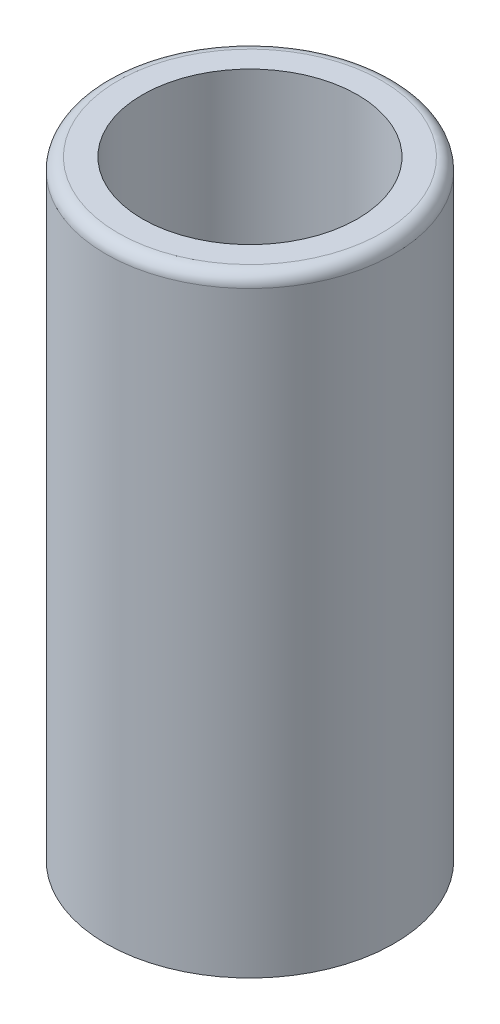
SolidWorks part; units mm, degrees
ref_plane "Front Plane" through (0, 0, 0) normal (0, 0, 1) x (1, 0, 0)
ref_plane "Top Plane" through (0, 0, 0) normal (0, 1, 0) x (1, 0, 0)
ref_plane "Right Plane" through (0, 0, 0) normal (1, 0, 0) x (0, 0, -1)
sketch "Sketch1" plane through (0, 0, 0) normal (0, 1, 0) x (1, 0, 0)
  circle A0 centre (0, 0) radius 11.825
  dimension "D1" = 23.65
extrude "Main Structure" add sketch "Sketch1" along normal blind 50
sketch "Sketch2" plane through (0, 50, 0) normal (0, 1, 0) x (1, 0, 0)
  circle A0 centre (0, 0) radius 8.825
  dimension "D1" = 17.65
extrude "Hole" cut sketch "Sketch2" against normal blind 15.5
fillet "Structure Fillet" radius 1 1 edges at (0, 50, 11.825)
sketch "Sketch3" plane through (0, 0, 0) normal (0, -1, 0) x (1, 0, 0)
  circle A0 centre (0, 0) radius 0.795
  dimension "D1" = 1.59
extrude "Cut-Extrude1" cut sketch "Sketch3" against normal up to next
